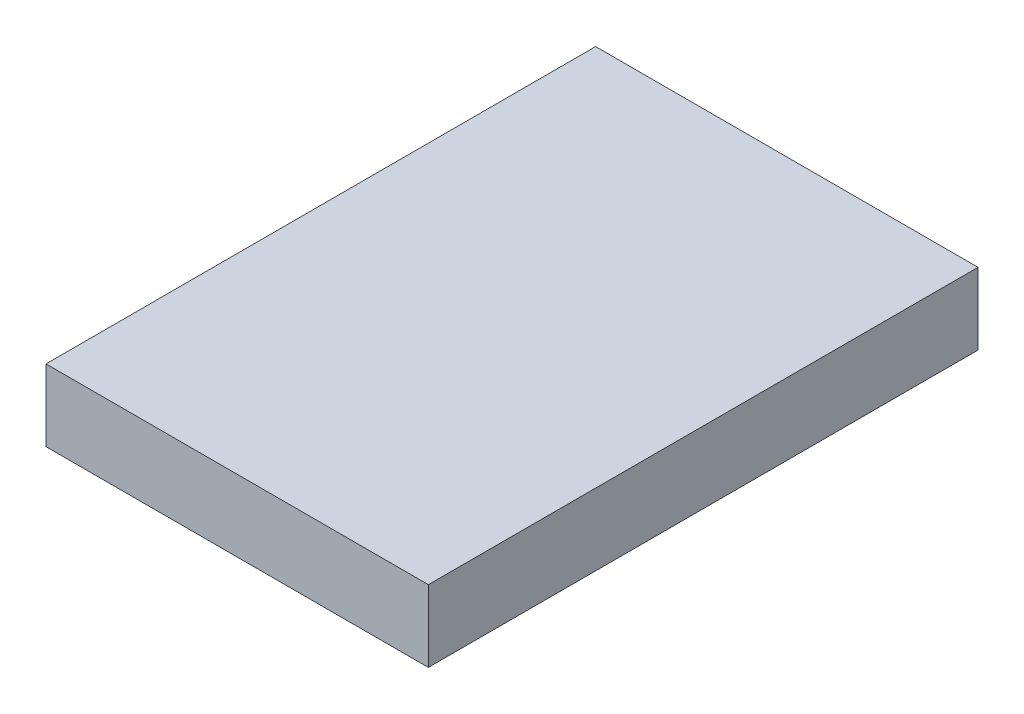
SolidWorks part; units mm, degrees
ref_plane "Front Plane" through (0, 0, 0) normal (0, 0, 1) x (1, 0, 0)
ref_plane "Top Plane" through (0, 0, 0) normal (0, 1, 0) x (1, 0, 0)
ref_plane "Right Plane" through (0, 0, 0) normal (1, 0, 0) x (0, 0, -1)
sketch "Sketch2" plane through (0, 0, 0) normal (0, 1, 0) x (1, 0, 0)
  line L1 (0, 0) -> (101.6, 0)
  line L2 (0, 0) -> (0, 146.05)
  line L3 (0, 146.05) -> (101.6, 146.05)
  line L4 (101.6, 0) -> (101.6, 146.05)
  dimension "D1" = 101.6
  dimension "D2" = 146.05
extrude "Boss-Extrude1" add sketch "Sketch2" along normal blind 19.05
